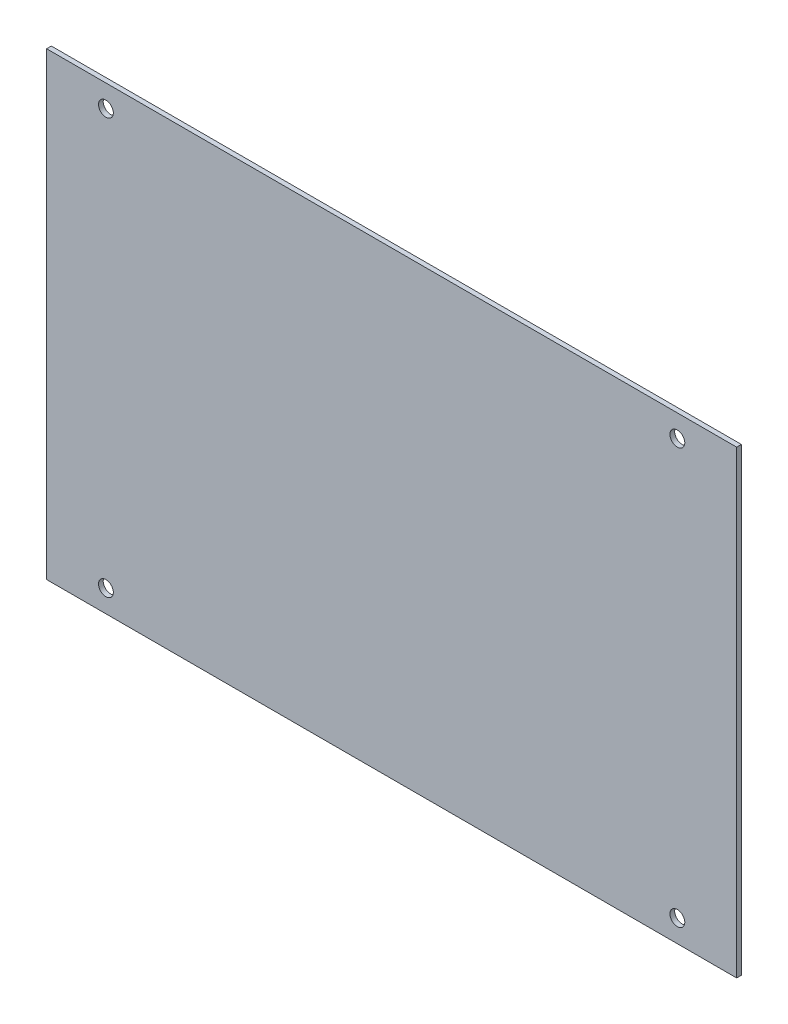
SolidWorks part; units mm, degrees
material "6061 Alloy"
ref_plane "Front Plane" through (0, 0, 0) normal (0, 0, 1) x (1, 0, 0)
ref_plane "Top Plane" through (0, 0, 0) normal (0, 1, 0) x (1, 0, 0)
ref_plane "Right Plane" through (0, 0, 0) normal (1, 0, 0) x (0, 0, -1)
sketch "Sketch1" plane through (0, 0, 0) normal (0, 0, 1) x (1, 0, 0)
  line L0 (-82.7574, 17.7712) -> (-82.7574, -137.2288)
  line L3 (-82.7574, 17.7712) -> (149.9102, 17.7712)
  line L4 (149.9102, 17.7712) -> (149.9102, -137.2288)
  line L5 (149.9102, -137.2288) -> (-82.7574, -137.2288)
  dimension "D1" = 155
  dimension "D2" = 232.6677
extrude "Boss-Extrude1" add sketch "Sketch1" along normal blind 1.5875 contours L3 L4 L5 L0
sketch "Sketch6" plane through (0, 0, 1.5875) normal (0, 0, 1) x (1, 0, 0)
  line L0 (-82.7574, 17.7712) -> (-82.7574, -137.2288) construction
  line L1 (-82.7574, 17.7712) -> (149.9102, 17.7712) construction
  line L2 (149.9102, 17.7712) -> (149.9102, -137.2288) construction
  line L3 (149.9102, -137.2288) -> (-82.7574, -137.2288) construction
  circle A0 centre (-62.7574, 10.2712) radius 2.5
  circle A1 centre (129.9102, 10.2712) radius 2.5
  circle A2 centre (-62.7574, -129.7288) radius 2.5
  circle A3 centre (129.9102, -129.7288) radius 2.5
  dimension "D1" = 20
  dimension "D3" = 7.5
  dimension "D5" = 20
  dimension "D2" = 7.5
  dimension "D4" = 20
  dimension "D6" = 7.5
extrude "Cut-Extrude1" cut sketch "Sketch6" against normal through all
